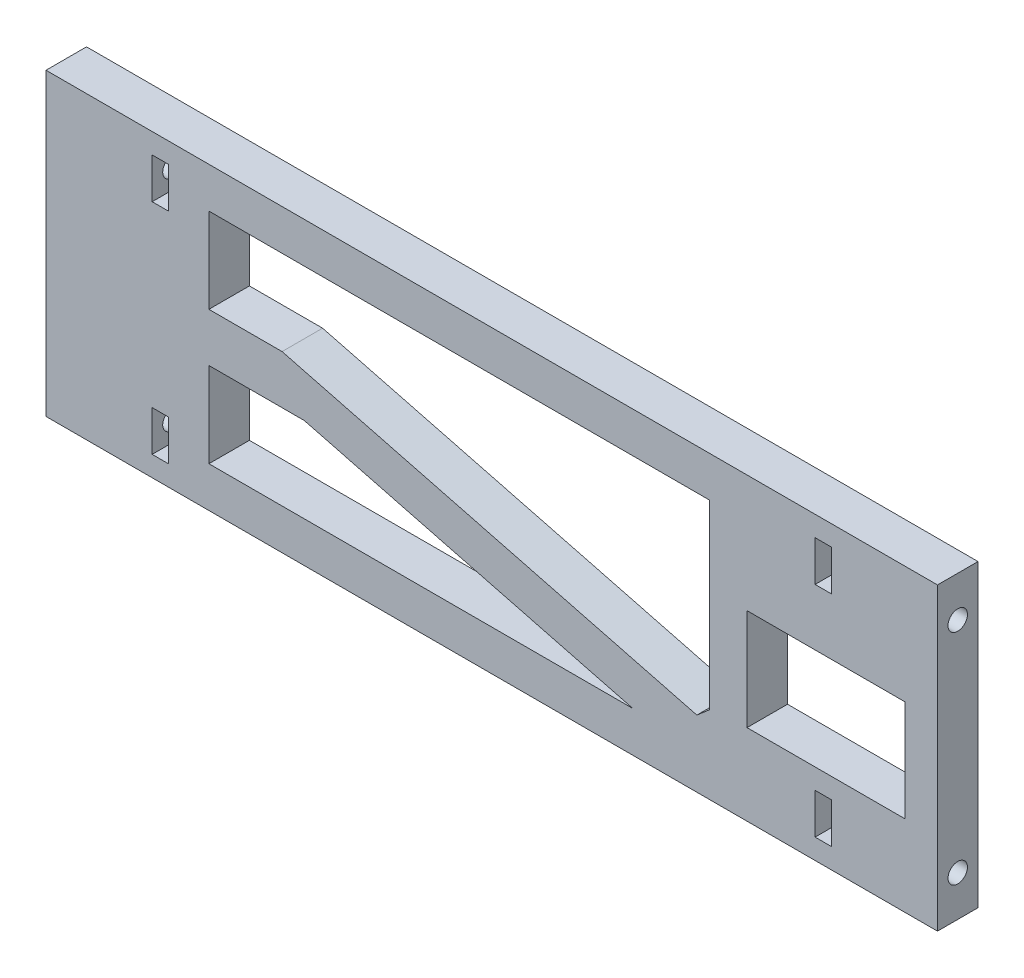
SolidWorks part; units mm, degrees
ref_plane "Front Plane" through (0, 0, 0) normal (0, 0, 1) x (1, 0, 0)
ref_plane "Top Plane" through (0, 0, 0) normal (0, 1, 0) x (1, 0, 0)
ref_plane "Right Plane" through (0, 0, 0) normal (1, 0, 0) x (0, 0, -1)
sketch "Sketch1" plane through (0, 0, 0) normal (0, 0, 1) x (1, 0, 0)
  line L0 (-55, 18.5) -> (-58, 18.5) construction
  line L1 (-55, -18.5) -> (55, -18.5)
  line L2 (-55, -18.5) -> (-55, 18.5)
  line L3 (-55, 18.5) -> (55, 18.5)
  line L4 (55, -18.5) -> (55, 18.5)
  line L5 (-55, -18.5) -> (55, 18.5) construction
  line L6 (-55, 18.5) -> (55, -18.5) construction
  point P0 (0, 0)
  dimension "D2" = 110
extrude "Boss-Extrude1" add sketch "Sketch1" along normal blind 5
hole_wizard "M2 Clearance Hole1" positions "Sketch2" profile "Sketch4" hole size "M2" standard "ANSI Metric"
sketch "Sketch2" plane through (-55, 0, 0) normal (-1, 0, 0) x (0, 0, 1)
  point P0 (2.5, 13.5)
  point P3 (2.5, -13.5)
sketch "Sketch4" plane through (-55, 13.5, 2.5) normal (0, 1, 0) x (0, 0, 1)
  line L0 (0, 0) -> (0, 14.721)
  line L1 (0, 14.721) -> (1.2, 14)
  line L2 (1.2, 14) -> (1.2, 0)
  line L5 (1.2, 0) -> (0, 0)
  line L10 (0, 14.721) -> (-1.2, 14) construction
  line L11 (0, -6.35) -> (0, 107.95) construction
  dimension "Hole Dia." = 2.4
  dimension "Hole Depth" = 14
  dimension "Drill Angle" = 118
sketch "Sketch5" plane through (0, 0, 5) normal (0, 0, 1) x (1, 0, 0)
  line L0 (-58, -10.5) -> (-58, -16.5) construction
  line L1 (-58, 16.5) -> (-58, 10.5) construction
  line L2 (-58, -10.5) -> (-58, -16.5)
  line L3 (-58, 16.5) -> (-58, 10.5)
  line L9 (-41.9, -11) -> (-39.9, -11)
  line L10 (-41.9, -11) -> (-41.9, -16)
  line L11 (-41.9, -16) -> (-39.9, -16)
  line L12 (-39.9, -11) -> (-39.9, -16)
  line L13 (-41.9, 11) -> (-39.9, 11)
  line L14 (-41.9, 11) -> (-41.9, 16)
  line L15 (-41.9, 16) -> (-39.9, 16)
  line L16 (-39.9, 11) -> (-39.9, 16)
  line L17 (-55.9, 15.1583) -> (-55.9, 11.8417) construction
  point P12 (-41.9, 13.5)
  point P13 (-58, 13.5)
  point P14 (-41.9, -13.5)
  point P15 (-58, -13.5)
  dimension "D1" = 5
  dimension "D2" = 16
  dimension "D3" = 2
extrude "Cut-Extrude1" cut sketch "Sketch5" against normal blind 4 contours L13 L16 L15 L14 | L12 L9 L10 L11
mirror "Mirror1" about plane through (0, 0, 0) normal (1, 0, 0) of "M2 Clearance Hole1", "Cut-Extrude1"
sketch "Sketch6" plane through (0, 0, 5) normal (0, 0, 1) x (1, 0, 0)
  line L0 (31.5, -8.5) -> (51, -8.5)
  line L1 (51, -8.5) -> (51, 4)
  line L2 (51, 4) -> (31.5, 4)
  line L3 (31.5, 4) -> (31.5, -8.5)
  line L5 (55, -18.5) -> (55, 18.5) construction
  line L6 (-55, -18.5) -> (55, -18.5) construction
  dimension "D1" = 19.5
  dimension "D2" = 12.5
  dimension "D3" = 4
  dimension "D4" = 10
extrude "Cut-Extrude2" cut sketch "Sketch6" against normal blind 10
sketch "Sketch7" plane through (0, 0, 5) normal (0, 0, 1) x (1, 0, 0)
  line L0 (-39.9, 11) -> (-39.9, 16) construction
  line L1 (-34.9, -13.5) -> (26.9, -13.5)
  line L2 (-34.9, -13.5) -> (-34.9, 13.5)
  line L3 (-34.9, 13.5) -> (26.9, 13.5)
  line L4 (55, -18.5) -> (55, 18.5)
  line L5 (55, 18.5) -> (-55, 18.5)
  line L6 (-55, 18.5) -> (-55, -18.5)
  line L7 (-55, -18.5) -> (55, -18.5)
  line L8 (55, -18.5) -> (55, 18.5)
  line L9 (55, 18.5) -> (-55, 18.5)
  line L11 (-55, -18.5) -> (55, -18.5)
  line L12 (26.9, -13.5) -> (26.9, 13.5)
  line L13 (39.9, 11) -> (39.9, 16) construction
  line L43 (-56, 3) -> (-25.8726, 3)
  line L44 (-25.8726, 3) -> (27.1507, -10.7292)
  line L45 (32.7493, -17.4681) -> (-23.1274, -3)
  line L46 (-23.1274, -3) -> (-56, -3)
  line L47 (25.3101, -10.2527) -> (26.9, -8.8787)
  line L48 (-23, -2) -> (-56, -2)
  line L49 (-58, -4) -> (-58, -18.5)
  line L50 (-26, 2) -> (23.748, -10.8812)
  line L51 (27.5, -7.977) -> (27.5, 8)
  line L52 (27.5, 8) -> (58, 8)
  line L53 (58, 8) -> (58, 18.5)
  line L54 (58, 18.5) -> (-58, 18.5)
  line L55 (-58, 18.5) -> (-58, 4)
  line L56 (-56, 2) -> (-26, 2)
  line L57 (-26, 2) -> (26.9, -11.6973)
  line L63 (-56, 2) -> (-26, 2)
  line L64 (-58, -18.5) -> (58, -18.5)
  line L65 (56, -16.5) -> (33, -16.5)
  line L66 (33, -16.5) -> (-23, -2)
  line L67 (-23, -2) -> (-56, -2)
  line L70 (56, -16.5) -> (33, -16.5)
  line L71 (33, -16.5) -> (-23, -2)
  arc A12 (23.748, -10.8812) -> (27.5, -7.977) centre (24.5, -7.977) ccw
  arc A13 (-58, 4) -> (-56, 2) centre (-56, 4) ccw
  arc A16 (-56, -2) -> (-58, -4) centre (-56, -4) ccw
  arc A17 (58, -18.5) -> (56, -16.5) centre (56, -18.5) ccw
  dimension "D2" = 5
  dimension "D3" = 5
  dimension "D4" = 5
  dimension "D5" = 13
  dimension "D6" = 0
  dimension "D1" = 0
  dimension "D7" = 0
  dimension "D8" = 1
extrude "Cut-Extrude3" cut sketch "Sketch7" against normal through all contours L45 L46 L2 L1 | L44 L47 L12 L3 L2 L43
